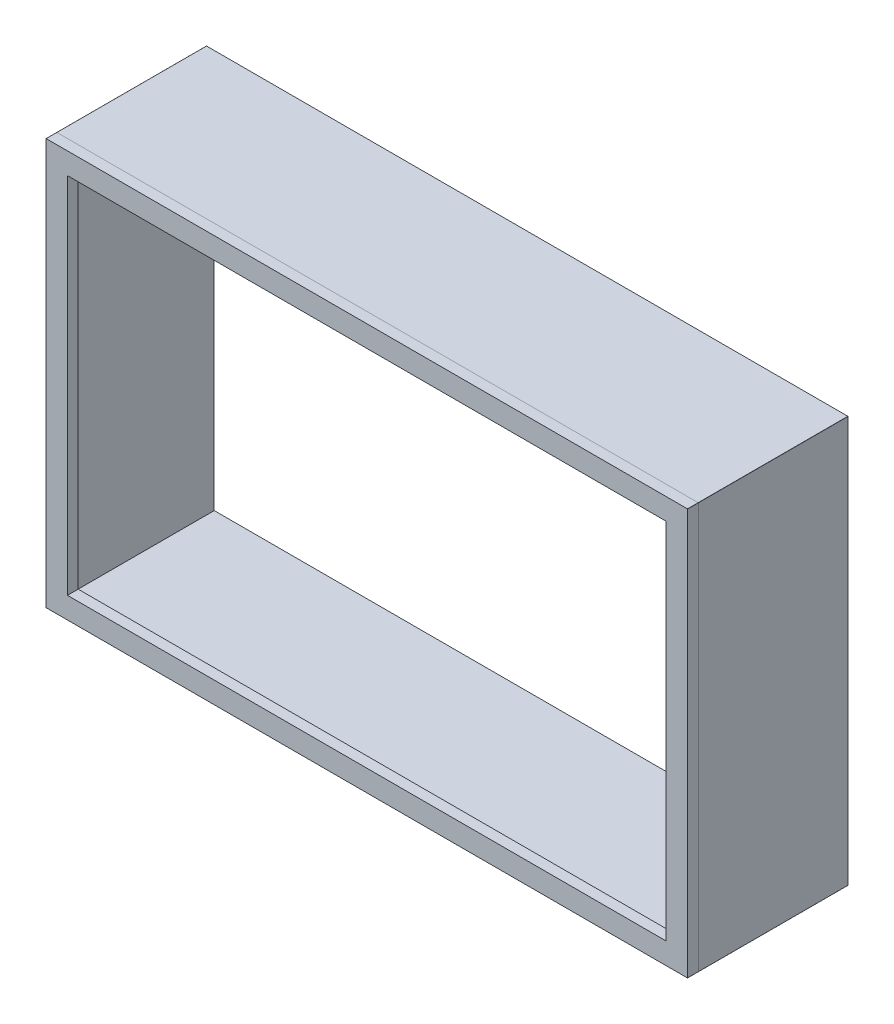
SolidWorks part; units mm, degrees
ref_plane "Front Plane" through (0, 0, 0) normal (0, 0, 1) x (1, 0, 0)
ref_plane "Top Plane" through (0, 0, 0) normal (0, 1, 0) x (1, 0, 0)
ref_plane "Right Plane" through (0, 0, 0) normal (1, 0, 0) x (0, 0, -1)
sketch "Sketch1" plane through (0, 0, 0) normal (0, 0, 1) x (1, 0, 0)
  line L1 (761.746, -482.6) -> (-761.746, -482.6)
  line L2 (762, -482.346) -> (762, 482.346)
  line L3 (761.746, 482.6) -> (-761.746, 482.6)
  line L4 (-762, -482.346) -> (-762, 482.346)
  line L5 (762, -482.6) -> (-762, 482.6) construction
  line L6 (762, 482.6) -> (-762, -482.6) construction
  arc A0 (-761.746, -482.6) -> (-762, -482.346) centre (-761.746, -482.346) cw
  arc A1 (761.746, -482.6) -> (762, -482.346) centre (761.746, -482.346) ccw
  arc A2 (762, 482.346) -> (761.746, 482.6) centre (761.746, 482.346) ccw
  arc A3 (-761.746, 482.6) -> (-762, 482.346) centre (-761.746, 482.346) ccw
  point P0 (0, 0)
  dimension "D3" = 0.254
  dimension "D1" = 1524
  dimension "D2" = 965.2
extrude "Extrude-Thin1" add sketch "Sketch1" along normal blind 203.2 and the other way blind 152.4 thin
sketch "Sketch2" plane through (0, 0, 203.2) normal (0, 0, 1) x (1, 0, 0)
  line L4 (-762, 482.346) -> (-762, -482.346)
  line L5 (-761.746, -482.6) -> (761.746, -482.6)
  line L6 (762, -482.346) -> (762, 482.346)
  line L7 (761.746, 482.6) -> (-761.746, 482.6)
  line L8 (-762, 482.346) -> (-762, -482.346)
  line L9 (-761.746, -482.6) -> (761.746, -482.6)
  line L10 (762, -482.346) -> (762, 482.346)
  line L11 (761.746, 482.6) -> (-761.746, 482.6)
  arc A4 (-762, -482.346) -> (-761.746, -482.6) centre (-761.746, -482.346) ccw
  arc A5 (-762, -482.346) -> (-761.746, -482.6) centre (-761.746, -482.346) ccw
  arc A6 (761.746, -482.6) -> (762, -482.346) centre (761.746, -482.346) ccw
  arc A7 (761.746, -482.6) -> (762, -482.346) centre (761.746, -482.346) ccw
  arc A8 (762, 482.346) -> (761.746, 482.6) centre (761.746, 482.346) ccw
  arc A9 (762, 482.346) -> (761.746, 482.6) centre (761.746, 482.346) ccw
  arc A10 (-761.746, 482.6) -> (-762, 482.346) centre (-761.746, 482.346) ccw
  arc A11 (-761.746, 482.6) -> (-762, 482.346) centre (-761.746, 482.346) ccw
  dimension "D1" = 0
extrude "Extrude-Thin2" add sketch "Sketch2" along normal blind 25.4 separate body thin
